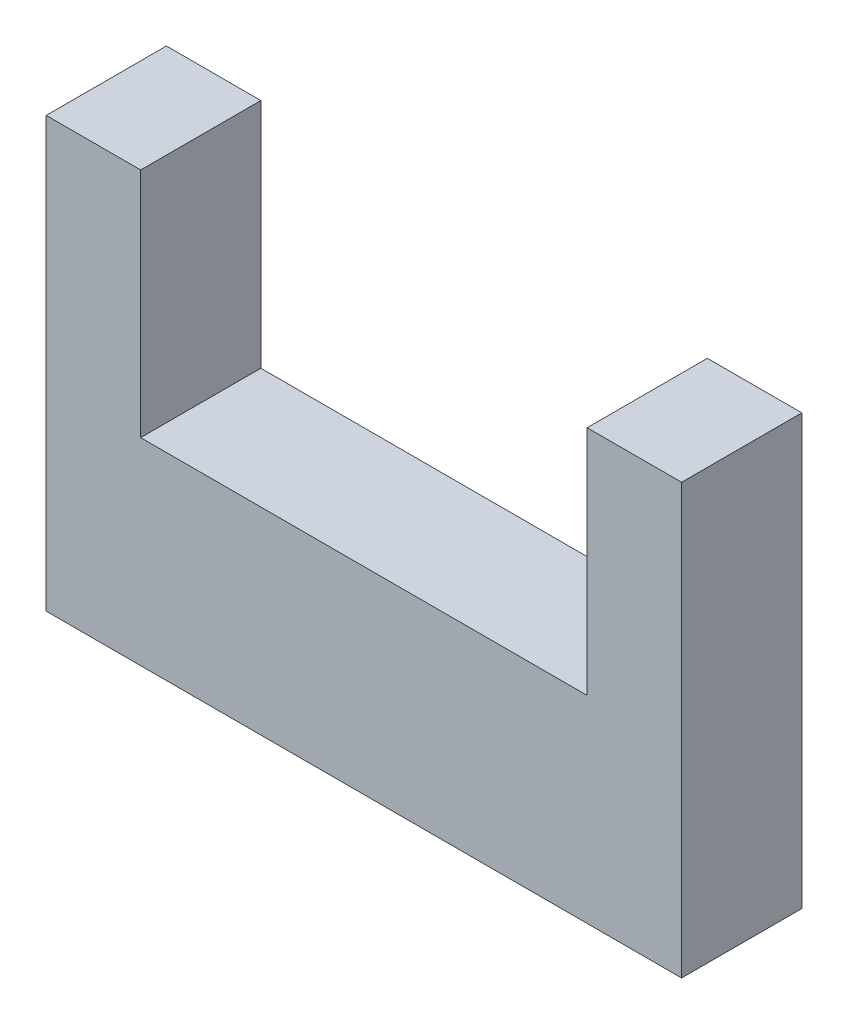
SolidWorks part; units mm, degrees
ref_plane "Front Plane" through (0, 0, 0) normal (0, 0, 1) x (1, 0, 0)
ref_plane "Top Plane" through (0, 0, 0) normal (0, 1, 0) x (1, 0, 0)
ref_plane "Right Plane" through (0, 0, 0) normal (1, 0, 0) x (0, 0, -1)
sketch "Sketch1" plane through (0, 0, 0) normal (0, 0, 1) x (1, 0, 0)
  line L0 (14.5, 67.2609) -> (14.5, 80.7609)
  line L3 (-17, 55.7609) -> (20, 55.7609)
  line L5 (14.5, 80.7609) -> (20, 80.7609)
  line L8 (-17, 80.7609) -> (-11.5, 80.7609)
  line L9 (-11.5, 80.7609) -> (-11.5, 67.2609)
  line L10 (-11.5, 67.2609) -> (14.5, 67.2609)
  line L11 (20, 80.7609) -> (20, 55.7609)
  line L12 (-17, 55.7609) -> (-17, 80.7609)
  point P0 (0, 0)
  dimension "D1" = 13.5
  dimension "D2" = 25
  dimension "D3" = 26
  dimension "D4" = 5.5
  dimension "D5" = 5.5
extrude "Boss-Extrude1" add sketch "Sketch1" against normal blind 7
